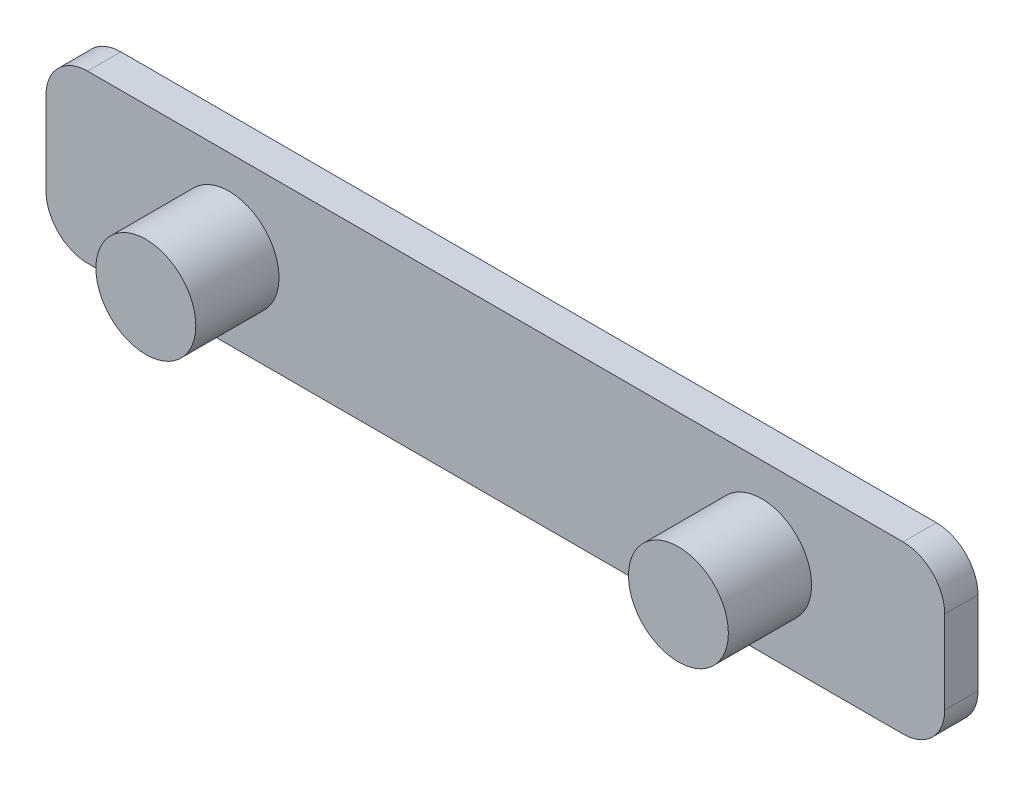
SolidWorks part; units mm, degrees
ref_plane "Front Plane" through (0, 0, 0) normal (0, 0, 1) x (1, 0, 0)
ref_plane "Top Plane" through (0, 0, 0) normal (0, 1, 0) x (1, 0, 0)
ref_plane "Right Plane" through (0, 0, 0) normal (1, 0, 0) x (0, 0, -1)
sketch "Sketch1" plane through (0, 0, 0) normal (0, 0, 1) x (1, 0, 0)
  line L1 (-5.3133, 3.8394) -> (43.6867, 3.8394)
  line L2 (-7.8133, 1.3394) -> (-7.8133, -3.6606)
  line L3 (-5.3133, -6.1606) -> (43.6867, -6.1606)
  line L4 (46.1867, 1.3394) -> (46.1867, -3.6606)
  arc A0 (-7.8133, 1.3394) -> (-5.3133, 3.8394) centre (-5.3133, 1.3394) cw
  arc A1 (-7.8133, -3.6606) -> (-5.3133, -6.1606) centre (-5.3133, -3.6606) ccw
  arc A2 (46.1867, -3.6606) -> (43.6867, -6.1606) centre (43.6867, -3.6606) cw
  arc A3 (46.1867, 1.3394) -> (43.6867, 3.8394) centre (43.6867, 1.3394) ccw
  point P6 (-7.8133, 3.8394)
  point P9 (-7.8133, -6.1606)
  point P14 (46.1867, 3.8394)
  dimension "D3" = 2.5
  dimension "D4" = 2.5
  dimension "D5" = 2.5
  dimension "D6" = 2.5
  dimension "D1" = 54
  dimension "D2" = 10
extrude "Boss-Extrude1" add sketch "Sketch1" along normal blind 2
sketch "Sketch2" plane through (0, 0, 2) normal (0, 0, 1) x (1, 0, 0)
  line L0 (-5.3133, -6.1606) -> (43.6867, -6.1606) construction
  line L1 (-7.8133, 1.3394) -> (-7.8133, -3.6606) construction
  circle A0 centre (3.1867, -1.1606) radius 3
  circle A1 centre (35.1867, -1.1606) radius 3
  dimension "D2" = 6
  dimension "D1" = 32
  dimension "D3" = 5
  dimension "D4" = 11
extrude "Boss-Extrude2" add sketch "Sketch2" along normal blind 5
